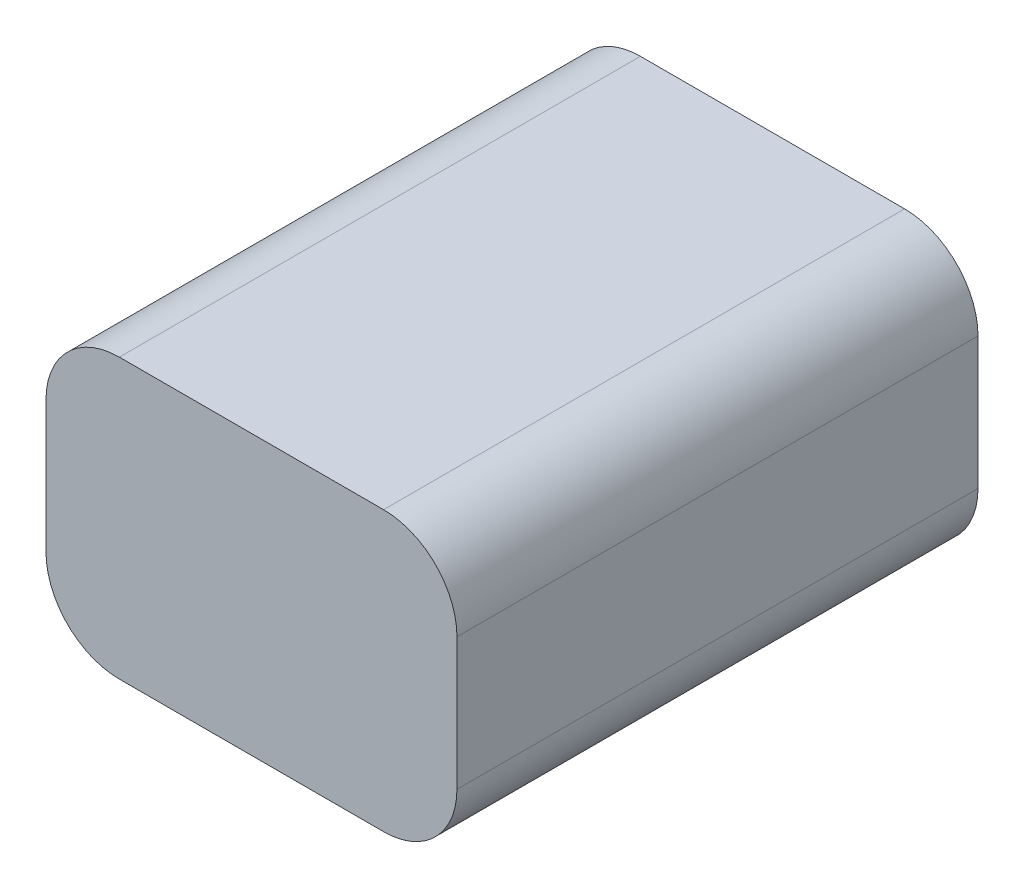
SolidWorks part; units mm, degrees
ref_plane "前视基准面" through (0, 0, 0) normal (0, 0, 1) x (1, 0, 0)
ref_plane "上视基准面" through (0, 0, 0) normal (0, 1, 0) x (1, 0, 0)
ref_plane "右视基准面" through (0, 0, 0) normal (1, 0, 0) x (0, 0, -1)
other "Configuration Table"
sketch "草图1" plane through (0, 0, 0) normal (0, 0, 1) x (1, 0, 0)
  line L1 (0, 0) -> (56, 0)
  line L2 (0, 0) -> (0, 38)
  line L3 (0, 38) -> (56, 38)
  line L4 (56, 0) -> (56, 38)
  dimension "D1" = 56
  dimension "D2" = 38
extrude "凸台-拉伸1" add sketch "草图1" along normal blind 71
fillet "圆角1" radius 10 4 edges at (56, 0, 35.5) (0, 0, 35.5) (0, 38, 35.5) (56, 38, 35.5)
